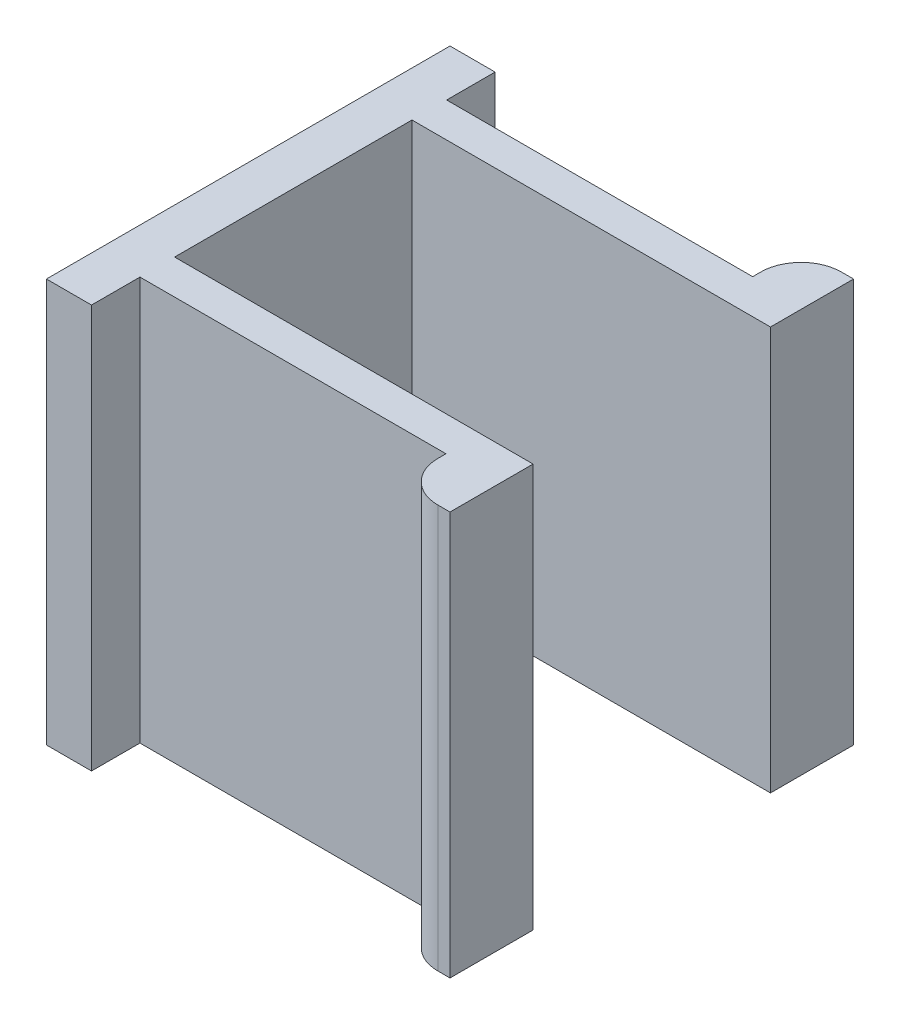
SolidWorks part; units mm, degrees
material "Maple"
ref_plane "Front" through (0, 0, 0) normal (0, 0, 1) x (1, 0, 0)
ref_plane "Top" through (0, 0, 0) normal (0, 1, 0) x (1, 0, 0)
ref_plane "Right" through (0, 0, 0) normal (1, 0, 0) x (0, 0, -1)
sketch "Sketch2" plane through (0, 0, 0) normal (0, 0, 1) x (1, 0, 0)
  line L1 (-50, 100) -> (50, 100)
  line L2 (-50, 100) -> (-50, 0)
  line L3 (-50, 0) -> (50, 0)
  line L4 (50, 100) -> (50, 0)
  line L5 (-50, 100) -> (50, 0) construction
  line L6 (-50, 0) -> (50, 100) construction
  point P4 (0, 50)
  dimension "D1" = 100
  dimension "D2" = 100
extrude "Boss-Extrude2" add sketch "Sketch2" along normal blind 100
sketch "Sketch4" plane through (0, 100, 0) normal (0, 1, 0) x (1, 0, 0)
  line L0 (-38.8271, -100) -> (-38.8271, -88)
  line L1 (50, -100) -> (-50, -100) construction
  line L2 (-38.8271, -88) -> (37, -88)
  line L3 (37, -88) -> (37, -90)
  line L4 (47, -100) -> (50, -100)
  line L5 (50, -100) -> (50, -79.4107)
  line L6 (50, -100) -> (50, 0) construction
  line L7 (50, -79.4107) -> (-38.8271, -79.4107)
  line L8 (-38.8271, -79.4107) -> (-38.8271, -20.5893)
  line L9 (-38.8271, -100) -> (-50, -100)
  line L10 (-50, -100) -> (-50, 0)
  line L11 (-50, -100) -> (-50, 0) construction
  line L12 (-50, 0) -> (-38.8271, 0)
  line L13 (50, -20.5893) -> (-38.8271, -20.5893)
  line L14 (37, -12) -> (37, -10)
  line L15 (-38.8271, -12) -> (37, -12)
  line L16 (-38.8271, 0) -> (-38.8271, -12)
  line L17 (50, -20.5893) -> (50, 0)
  line L18 (50, 0) -> (47, 0)
  line L19 (-50, -100) -> (-50, 0)
  line L20 (-50, -100) -> (-38.8271, -100)
  line L21 (-38.8271, -100) -> (-38.8271, -88)
  arc A0 (37, -90) -> (47, -100) centre (47, -90) ccw
  arc A1 (37, -10) -> (47, 0) centre (47, -10) cw
  point P21 (-38.8271, -50)
  point P28 (37, -100)
  point P33 (37, 0)
  line M7 (50, 0) -> (-50, 0)
  line M9 (-50, -100) -> (50, -100)
  line M10 (50, -100) -> (50, 0)
  dimension "D6" = 10
  dimension "D7" = 10
  dimension "D1" = 12
  dimension "D2" = 13
  dimension "D3" = 29.4107
  dimension "D4" = 12
  dimension "D5" = 75.8271
extrude "Cut-Extrude1" cut sketch "Sketch4" against normal blind 100 contours L13 L8 L7 M10 | A0 L3 L2 L0 M9 | L14 A1 L16 L15 M7
sketch "Sketch6" plane through (-50, 0, 0) normal (-1, 0, 0) x (0, 0, 1)
  line L1 (93.4827, 5.8627) -> (4.7488, 5.8627)
  line L2 (93.4827, 5.8627) -> (93.4827, 94.3658)
  line L3 (93.4827, 94.3658) -> (4.7488, 94.3658)
  line L4 (4.7488, 5.8627) -> (4.7488, 94.3658)
  line L5 (93.4827, 5.8627) -> (4.7488, 94.3658) construction
  line L6 (93.4827, 94.3658) -> (4.7488, 5.8627) construction
  point P4 (49.1157, 50.1143)
extrude "Boss-Extrude3" add sketch "Sketch6" along normal blind 3
